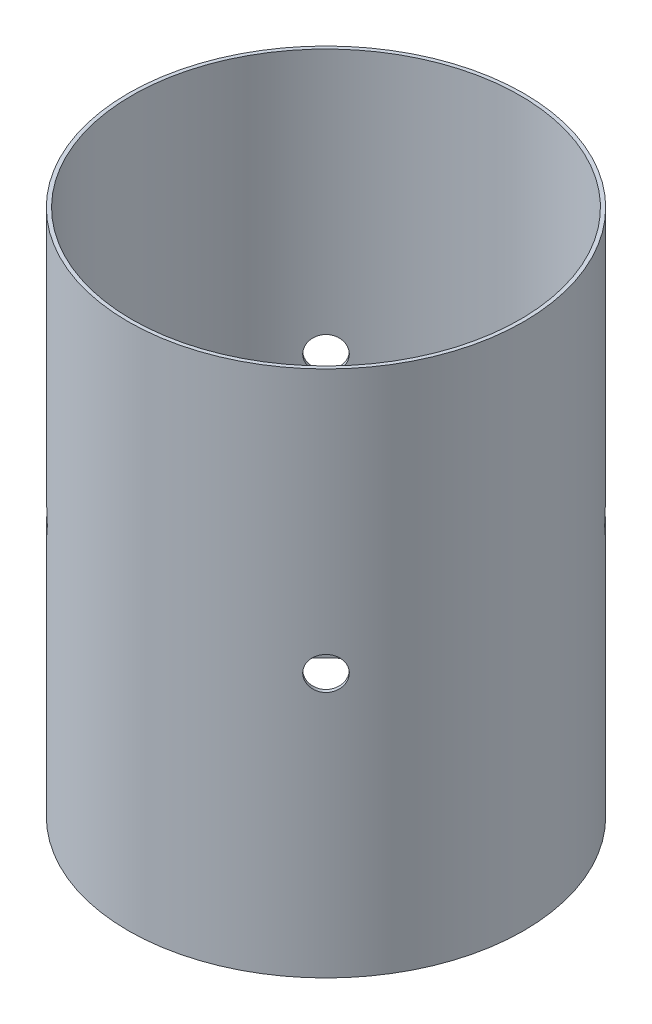
SolidWorks part; units mm, degrees
material "Thornel Mat VMA"
ref_plane "Front Plane" through (0, 0, 0) normal (0, 0, 1) x (1, 0, 0)
ref_plane "Top Plane" through (0, 0, 0) normal (0, 1, 0) x (1, 0, 0)
ref_plane "Right Plane" through (0, 0, 0) normal (1, 0, 0) x (0, 0, -1)
sketch "Sketch1" plane through (0, 0, 0) normal (0, 1, 0) x (1, 0, 0)
  circle A0 centre (0, 0) radius 74.7776
  circle A1 centre (0, 0) radius 76.2
  dimension "D1" = 149.5552
  dimension "D2" = 152.4
extrude "Boss-Extrude1" add sketch "Sketch1" along normal mid plane 203.2
extrude "Cut-Extrude1" cut sketch "Sketch2" against normal blind 5.08
sketch "Sketch2" plane through (54.8873, 0, -54.8873) normal (0.7071, 0, -0.7071) x (0, -1, 0)
  circle A0 centre (0, 0) radius 6.35
pattern_circular "CirPattern1" count 4 over 360 of "Cut-Extrude1"
equation "\"airframeInnerDiameter\"= 6in"
equation "\"outerDiameter\"= 6.112in"
equation "\"airframeBulkheadThickness\"= 0.125in"
equation "\"payloadAirframeLength\"= 10in"
equation "\"payloadInnerDiameter\"= 6in - 0.056in"
equation "\"payloadOuterDiameter\"= \"airframeInnerDiameter\""
equation "\"payloadLength\"= 11in"
equation "\"payloadBand\"= 2in"
equation "\"payloadOffsetFromAft\"= 6in"
equation "\"upperAirframeLength\"= 25in"
equation "\"recoveryBayInnerDiameter\"= 5.888in"
equation "\"recoveryLength\"= 8in"
equation "\"recoveryBand\"= 2in"
equation "\"recoveryCouplerOuter\"=\"airframeInnerDiameter\""
equation "\"recoveryOffsetFromAft\"= 3in"
equation "\"midAirframeLength\"= 20in"
equation "\"atsLength\"= 11in"
equation "\"atsInner\"= 5.888in"
equation "\"atsBand\"= 2in"
equation "\"atsCouplerOuter\"=\"airframeInnerDiameter\""
equation "\"atsOffsetFromAft\"= 3in"
equation "\"lowerAirframeLength\"= 40in"
equation "\"motorTubeOuterDiameter\"= 4.25in"
equation "\"motorTubeInnerDiameter\"= 4in"
equation "\"motorTubeLength\"= 32in"
equation "\"centeringRingOuterDiameter\"= \"airframeInnerDiameter\""
equation "\"centeringRingInnerDiameter\"= \"motorTubeOuterDiameter\""
equation "\"centeringRingThickness\"= 0.375in"
equation "\"topCenteringRingOffsetFromAft\"= 16.7in"
equation "\"bottomCenteringRingOffsetFromAft\"= 0.3in"
equation "\"finSlotLength\"= 8in"
equation "\"finSlotOffsetFromAft\"= 3in"
equation "\"finSlotWidth\"= 0.187in"
equation "\"motorCasingOuterDiameter\"= 3in"
equation "\"motorCasingCenteringRingThickness\"= 0.25in"
equation "\"D1@Sketch1\"=\"recoveryBayInnerDiameter\""
equation "\"D2@Sketch1\"=\"recoveryCouplerOuter\""
equation "\"D1@Boss-Extrude1\"=\"recoveryLength\""
